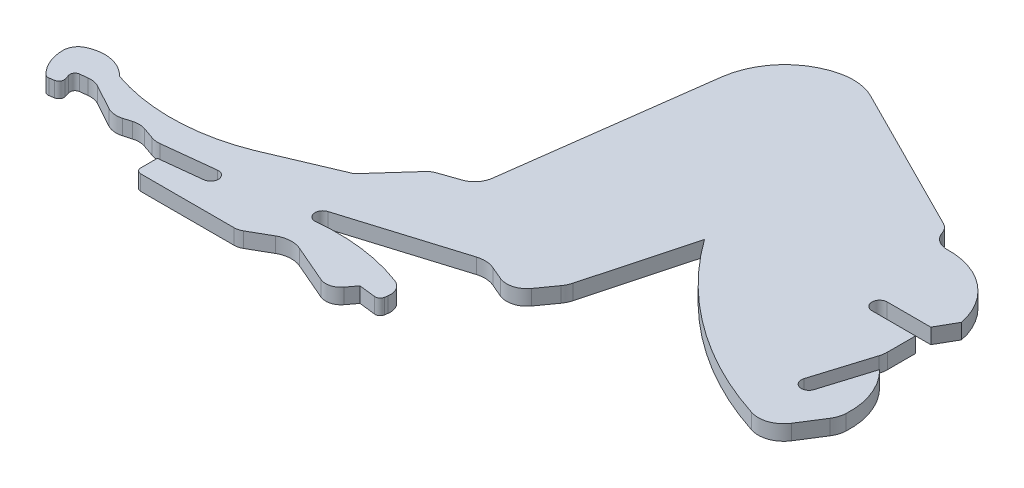
SolidWorks part; units mm, degrees
ref_plane "Front Plane" through (0, 0, 0) normal (0, 0, 1) x (1, 0, 0)
ref_plane "Top Plane" through (0, 0, 0) normal (0, 1, 0) x (1, 0, 0)
ref_plane "Right Plane" through (0, 0, 0) normal (1, 0, 0) x (0, 0, -1)
sketch "Sketch2" plane through (0, 0, 0) normal (0, 1, 0) x (1, 0, 0)
  line L0 (104.8617, 51.61) -> (96.2857, 51.61)
  line L1 (96.2857, 48.61) -> (104.8617, 48.61)
  line L2 (104.8617, 48.61) -> (104.8617, 42.36)
  line L3 (107.0706, 39.34) -> (104.0266, 29.4584)
  line L4 (101.1595, 30.3416) -> (104.8617, 42.36)
  line L5 (105.5312, 18.3607) -> (111.09, 27.1258)
  line L6 (104.8617, 51.61) -> (107.0706, 55.46)
  line L7 (89.7728, 69.8362) -> (57.4, 86.17)
  line L8 (41.6529, 73.6621) -> (36.03, 31.3784)
  line L9 (36.03, 31.3784) -> (29.1482, 28.9869)
  line L10 (29.1482, 28.9869) -> (21.9915, 21.0198)
  line L11 (21.9915, 21.0198) -> (8.1869, 15.1615)
  line L12 (0, 0) -> (0, 4.28)
  line L13 (0, 4.28) -> (8.2554, 5.2)
  line L14 (7.9231, 8.1815) -> (-3.1214, 6.9507)
  line L15 (-3.1214, 6.9507) -> (-7.4992, 8.4826)
  line L16 (-7.4992, 8.4826) -> (-11.8276, 7.2216)
  line L17 (-11.8276, 7.2216) -> (-19.2552, 11.2976)
  line L18 (-19.2552, 11.2976) -> (-23.2053, 10.8574)
  line L19 (-23.2053, 10.8574) -> (-22.2697, 7.6463)
  line L20 (-22.2697, 7.6463) -> (-24.8125, 7.2216)
  line L21 (0, 0) -> (20.16, 0)
  line L22 (20.16, 0) -> (27.0155, 3.9247)
  line L23 (27.0155, 3.9247) -> (38.9, -1.2)
  line L24 (38.9, -1.2) -> (41.66, 2.4827)
  line L25 (41.66, 2.4827) -> (45.9, 1.9915)
  line L26 (45.9, 1.9915) -> (46.4657, 5.8541)
  line L27 (25.83, 11.99) -> (49.95, 19.39)
  line L28 (49.95, 19.39) -> (57.13, 16.32)
  line L29 (57.13, 16.32) -> (61.9358, 23.0276)
  line L30 (61.9358, 23.0276) -> (67.6517, 44.29)
  arc A0 (96.2857, 51.61) -> (96.2857, 48.61) centre (96.2857, 50.11) ccw
  arc A1 (107.0706, 39.34) -> (111.09, 27.1258) centre (97.2099, 29.3266) cw
  arc A2 (104.0266, 29.4584) -> (101.1595, 30.3416) centre (102.5931, 29.9) cw
  arc A3 (107.0706, 55.46) -> (93.2591, 66.4439) centre (93.6334, 52.7391) ccw
  arc A4 (93.2591, 66.4439) -> (89.7728, 69.8362) centre (93.1665, 69.8362) cw
  arc A5 (57.4, 86.17) -> (41.6529, 73.6621) centre (56.0104, 71.7528) ccw
  arc A6 (8.1869, 15.1615) -> (-17.7049, 14.5311) centre (-5.6083, 49.7338) cw
  arc A7 (8.2554, 5.2) -> (7.9231, 8.1815) centre (8.0892, 6.6908) ccw
  arc A8 (-24.8125, 7.2216) -> (-27.5, 15.12) centre (-19.6156, 13.3963) cw
  arc A9 (-27.5, 15.12) -> (-17.7049, 14.5311) centre (-22.91, 9.71) cw
  arc A10 (46.4657, 5.8541) -> (26.4315, 9.0647) centre (30.5748, -29.1928) ccw
  arc A11 (26.4315, 9.0647) -> (25.83, 11.99) centre (26.27, 10.556) cw
  arc A12 (67.6517, 44.29) -> (105.5312, 18.3607) centre (122.4523, 83.7134) ccw
  point P4 (0, 0)
  point P9 (102.1515, 28.4665)
  point P12 (94.7857, 50.11)
  point P13 (-27.5, 15.12)
  point P62 (65.7252, 51.4333)
  point P63 (0, 0)
  point P64 (63.3961, 49.9334)
  point P65 (0, 0)
  point P66 (0, 0)
  point P67 (0, 0)
  point P68 (0, 0)
  point P69 (42.3753, -1.4259)
  point P70 (38.9, -1.0215)
  point P71 (0, 4.6593)
  point P72 (9.58, 6.8569)
  point P73 (0, 0)
  point P74 (0, 0)
  point P75 (45.0824, 5.4498)
  point P76 (0, 0)
  point P77 (0, 0)
  point P78 (0, 0)
  point P79 (60.2558, 48.9547)
  point P80 (0, 0)
  point P81 (0, 0)
  point P82 (-17.7049, 14.5311)
  point P83 (0, 0)
  point P84 (-27.5, 15.12)
  point P85 (0, 0)
  point P86 (-24.8125, 7.2216)
  point P87 (0, 0)
  point P88 (0, 0)
  point P89 (88.1603, 55.1676)
  point P90 (90.4793, 67.3146)
  point P91 (84.2293, 67.3146)
  point P92 (105.5312, 56.1614)
  point P93 (83.191, 68.198)
  point P94 (84.9579, 70.3319)
  point P95 (0, 0)
  point P96 (107.0706, 55.318)
  point P97 (0, 0)
  point P98 (100.2467, 52.925)
  point P99 (0, 0)
  point P100 (0, 0)
  point P101 (91.7572, 67.493)
  point P102 (89.6003, 67.3922)
  point P103 (90.555, 68.9468)
  point P104 (0, 0)
  point P105 (90.0628, 68.1859)
  point P106 (94.0793, 66.4417)
  point P107 (0, 0)
  point P108 (0, 0)
  point P109 (0, 0)
  point P110 (0, 0)
  point P111 (89.9959, 71.0462)
  point P112 (89.7728, 69.8362)
  point P113 (111.09, 27.1258)
  dimension "D6" = 1.5
  dimension "D11" = 1.5
  dimension "D32" = 14.0535
  dimension "D33" = 13.7098
  dimension "D34" = 3.3937
  dimension "D35" = 14.484
  dimension "D36" = 37.223
  dimension "D37" = 8.0706
  dimension "D38" = 7.0948
  dimension "D39" = 38.4812
  dimension "D40" = 67.5078
  dimension "D75" = 1.5
  dimension "D1" = 51.61
  dimension "D2" = 111.09
  dimension "D3" = 10.076
  dimension "D4" = 27.5
  dimension "D5" = 15.12
  dimension "D7" = 29.9
  dimension "D8" = 39.34
  dimension "D9" = 6.25
  dimension "D10" = 102.5931
  dimension "D12" = 4.28
  dimension "D13" = 20.16
  dimension "D14" = 5.14
  dimension "D15" = 1.2
  dimension "D16" = 45.9
  dimension "D17" = 38.9
  dimension "D18" = 86.17
  dimension "D19" = 9.58
  dimension "D20" = 5.2
  dimension "D21" = 11.99
  dimension "D22" = 16.32
  dimension "D23" = 57.13
  dimension "D24" = 49.95
  dimension "D25" = 26.27
  dimension "19.39" = 19.39
  dimension "D26" = 84.9
  dimension "D27" = 63.53
  dimension "D28" = 37.21
  dimension "D29" = 44.29
  dimension "D30" = 3.85
  dimension "D31" = 20
  dimension "D41" = 8.1869
  dimension "D42" = 21.9915
  dimension "D43" = 26.4315
  dimension "D44" = 27.0155
  dimension "D45" = 29.1482
  dimension "D46" = 41.6529
  dimension "D47" = 41.66
  dimension "D48" = 46.4657
  dimension "D49" = 56.0104
  dimension "D50" = 61.9358
  dimension "D51" = 67.6517
  dimension "D52" = 89.7728
  dimension "D53" = 97.2099
  dimension "D54" = 105.5312
  dimension "D55" = 122.4523
  dimension "D56" = 3.1214
  dimension "D57" = 5.6083
  dimension "D58" = 7.4992
  dimension "D59" = 11.8276
  dimension "D60" = 17.7049
  dimension "D61" = 19.2552
  dimension "D62" = 19.6156
  dimension "D63" = 22.2697
  dimension "D64" = 22.91
  dimension "D65" = 23.2053
  dimension "D66" = 24.8125
  dimension "D67" = 1.9915
  dimension "D68" = 2.4827
  dimension "D69" = 7.6463
  dimension "D70" = 8.4826
  dimension "D71" = 11.2976
  dimension "D72" = 21.0198
  dimension "D73" = 23.0276
  dimension "D74" = 28.9869
extrude "Boss-Extrude1" add sketch "Sketch2" along normal blind 3
fillet "Fillet1" radius 3 6 edges at (89.7728, 1.5, -69.8362) (29.1482, 1.5, -28.9869) (-27.5, 1.5, -15.12) (20.16, 1.5, 0) (46.4657, 1.5, -5.8541) (38.9, 1.5, 1.2)
fillet "Fillet2" radius 5 6 edges at (61.9358, 1.5, -23.0276) (49.95, 1.5, -19.39) (27.0155, 1.5, -3.9247) (104.8617, 1.5, -42.36) (111.09, 1.5, -27.1258) (105.5312, 1.5, -18.3607)
fillet "Fillet3" radius 4 6 edges at (36.03, 1.5, -31.3784) (-19.2552, 1.5, -11.2976) (-3.1214, 1.5, -6.9507) (-7.4992, 1.5, -8.4826) (-11.8276, 1.5, -7.2216) (57.13, 1.5, -16.32)
fillet "Fillet4" radius 1 5 edges at (45.9, 1.5, -1.9915) (0, 1.5, 0) (-24.8125, 1.5, -7.2216) (-22.2697, 1.5, -7.6463) (-23.2053, 1.5, -10.8574)
fillet "Fillet5" radius 10 1 edges at (57.4, 1.5, -86.17)
